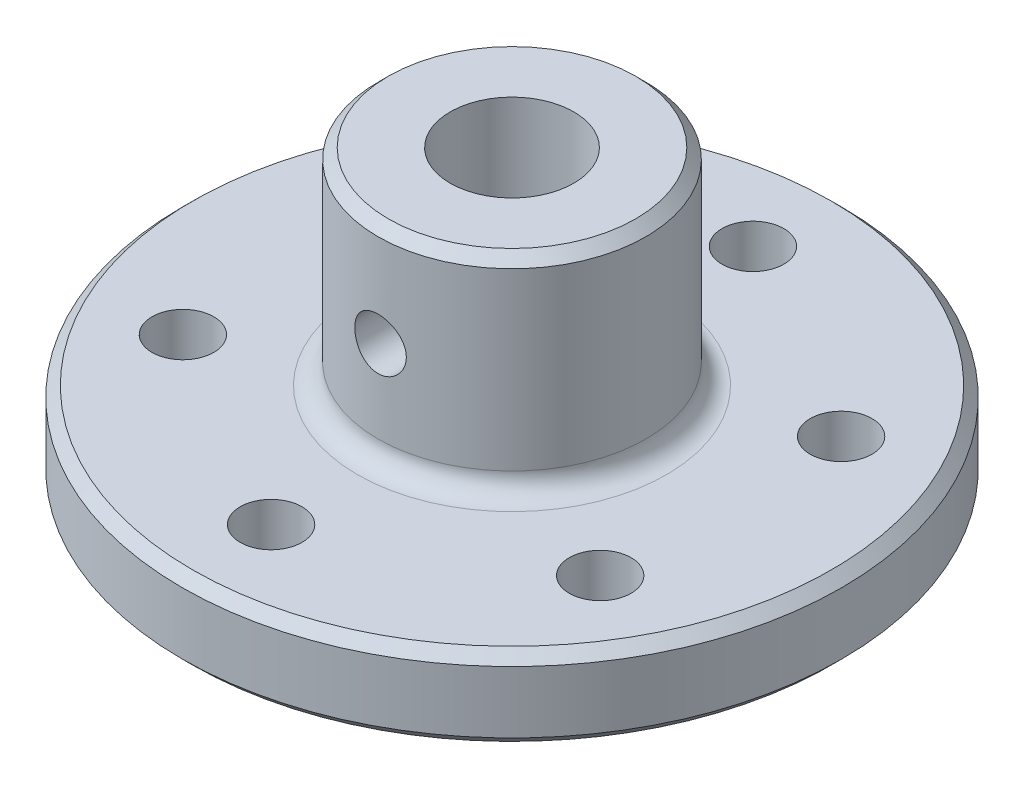
SolidWorks part; units mm, degrees
material "1023 Carbon Steel Sheet (SS)"
ref_plane "Front Plane" through (0, 0, 0) normal (0, 0, 1) x (1, 0, 0)
ref_plane "Top Plane" through (0, 0, 0) normal (0, 1, 0) x (1, 0, 0)
ref_plane "Right Plane" through (0, 0, 0) normal (1, 0, 0) x (0, 0, -1)
sketch "Sketch1" plane through (0, 0, 0) normal (0, 1, 0) x (1, 0, 0)
  line L1 (-10.125, 5.8457) -> (0, -11.6913) construction
  line L2 (0, -11.6913) -> (10.125, 5.8457) construction
  line L3 (10.125, 5.8457) -> (-10.125, 5.8457) construction
  circle A0 centre (0, 0) radius 16
  circle A2 centre (0, 11.6913) radius 1.5
  circle A3 centre (10.125, 5.8457) radius 1.5
  circle A4 centre (10.125, -5.8457) radius 1.5
  circle A5 centre (0, -11.6913) radius 1.5
  circle A6 centre (-10.125, -5.8457) radius 1.5
  circle A7 centre (-10.125, 5.8457) radius 1.5
  circle A8 centre (0, 0) radius 3
  circle A10 centre (0, 0) radius 5.8457 construction
  point P18 (0, 0)
  dimension "D1" = 32
  dimension "D2" = 20.25
  dimension "D3" = 3
  dimension "D5" = 6
  dimension "D4" = 6
extrude "Boss-Extrude1" add sketch "Sketch1" along normal blind 4
sketch "Sketch2" plane through (0, 4, 0) normal (0, 1, 0) x (1, 0, 0)
  circle A0 centre (0, 0) radius 3 construction
  circle A1 centre (0, 0) radius 3
  circle A2 centre (0, 0) radius 6.5
  dimension "D1" = 13
extrude "Boss-Extrude2" add sketch "Sketch2" along normal blind 10
fillet "Fillet1" radius 1 1 edges at (0, 4, 6.5)
sketch "Sketch3" plane through (0, 0, 0) normal (0, 0, 1) x (1, 0, 0)
  line L0 (16, 4) -> (-16, 4) construction
  circle A0 centre (0, 9) radius 1.25
  dimension "D1" = 2.5
  dimension "D2" = 5
extrude "Cut-Extrude1" cut sketch "Sketch3" against normal through all both and the other way through all
chamfer "Chamfer1" distance 0.5 angle 45 3 edges at (0, 0, 16) (0, 4, 16) (0, 14, 6.5)
